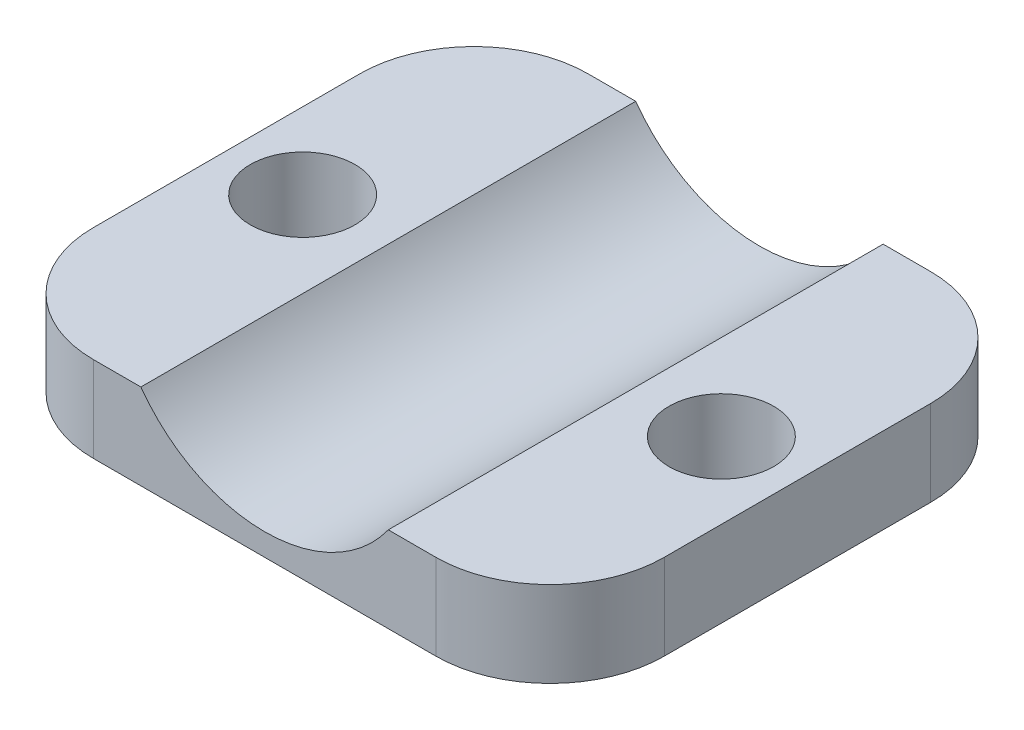
SolidWorks part; units mm, degrees
material "ABS PC"
ref_plane "Front Plane" through (0, 0, 0) normal (0, 0, 1) x (1, 0, 0)
ref_plane "Top Plane" through (0, 0, 0) normal (0, 1, 0) x (1, 0, 0)
ref_plane "Right Plane" through (0, 0, 0) normal (1, 0, 0) x (0, 0, -1)
sketch "Sketch1" plane through (0, 0, 0) normal (0, 1, 0) x (1, 0, 0)
  line L0 (0, 0) -> (0, 26)
  line L1 (0, 0) -> (30, 0)
  line L2 (0, 26) -> (30, 26)
  line L3 (30, 0) -> (30, 26)
  dimension "D1" = 30
  dimension "D2" = 26
extrude "Boss-Extrude1" add sketch "Sketch1" along normal blind 4.5
sketch "Sketch2" plane through (0, 0, 0) normal (0, 0, 1) x (1, 0, 0)
  line L0 (0, 4.5) -> (30, 4.5) construction
  line L1 (8.5, 4.5) -> (21.5, 4.5)
  line L2 (0, 4.5) -> (0, 0) construction
  line L3 (30, 4.5) -> (30, 0) construction
  arc A0 (8.5, 4.5) -> (21.5, 4.5) centre (15, 9.1637) ccw
  dimension "D1" = 8
  dimension "D2" = 8.5
  dimension "D3" = 8.5
extrude "Cut-Extrude1" cut sketch "Sketch2" against normal through all
hole_wizard "Ø5.5 (5.5) Diameter Hole1" positions "Sketch4" profile "Sketch3" hole size "Ø5.5" standard "Ansi Metric"
sketch "Sketch4" plane through (0, 4.5, 0) normal (0, 1, 0) x (-1, 0, 0)
  line L0 (0, -26) -> (0, 0) construction
  line L1 (-30, 0) -> (-30, -26) construction
  line L2 (-8.5, -26) -> (0, -26) construction
  point P0 (-4, -13)
  point P1 (-26, -13)
  dimension "D1" = 4
  dimension "D2" = 4
  dimension "D3" = 13
sketch "Sketch3" plane through (4, 4.5, -13) normal (1, 0, 0) x (0, 0, 1)
  line L0 (0, 0) -> (0, 11.6524)
  line L1 (0, 11.6524) -> (2.75, 10)
  line L2 (2.75, 10) -> (2.75, 0)
  line L5 (2.75, 0) -> (0, 0)
  line L10 (0, 11.6524) -> (-2.75, 10) construction
  line L11 (0, -6.35) -> (0, 107.95) construction
  dimension "Hole Dia." = 5.5
  dimension "Hole Depth" = 10
  dimension "Drill Angle" = 118
fillet "Fillet2" radius 6 4 edges at (0, 2.25, -26) (30, 2.25, -26) (0, 2.25, 0) (30, 2.25, 0)
